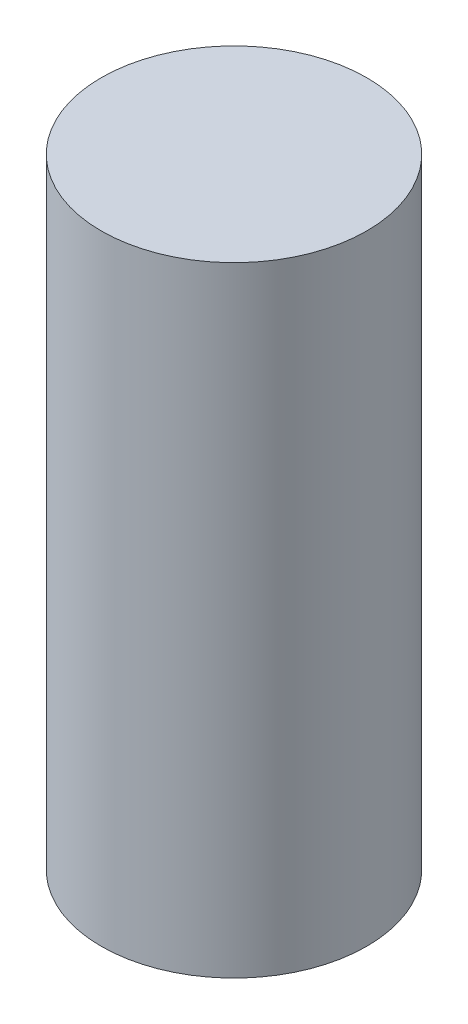
SolidWorks part; units mm, degrees
ref_plane "Front Plane" through (0, 0, 0) normal (0, 0, 1) x (1, 0, 0)
ref_plane "Top Plane" through (0, 0, 0) normal (0, 1, 0) x (1, 0, 0)
ref_plane "Right Plane" through (0, 0, 0) normal (1, 0, 0) x (0, 0, -1)
other "Configuration Table"
sketch "Sketch1" plane through (0, 0, 0) normal (0, 1, 0) x (1, 0, 0)
  circle A0 centre (650, 770) radius 6
extrude "OVEN_ayar_mil_4" add sketch "Sketch1" along normal blind 28 from offset 12 separate body
